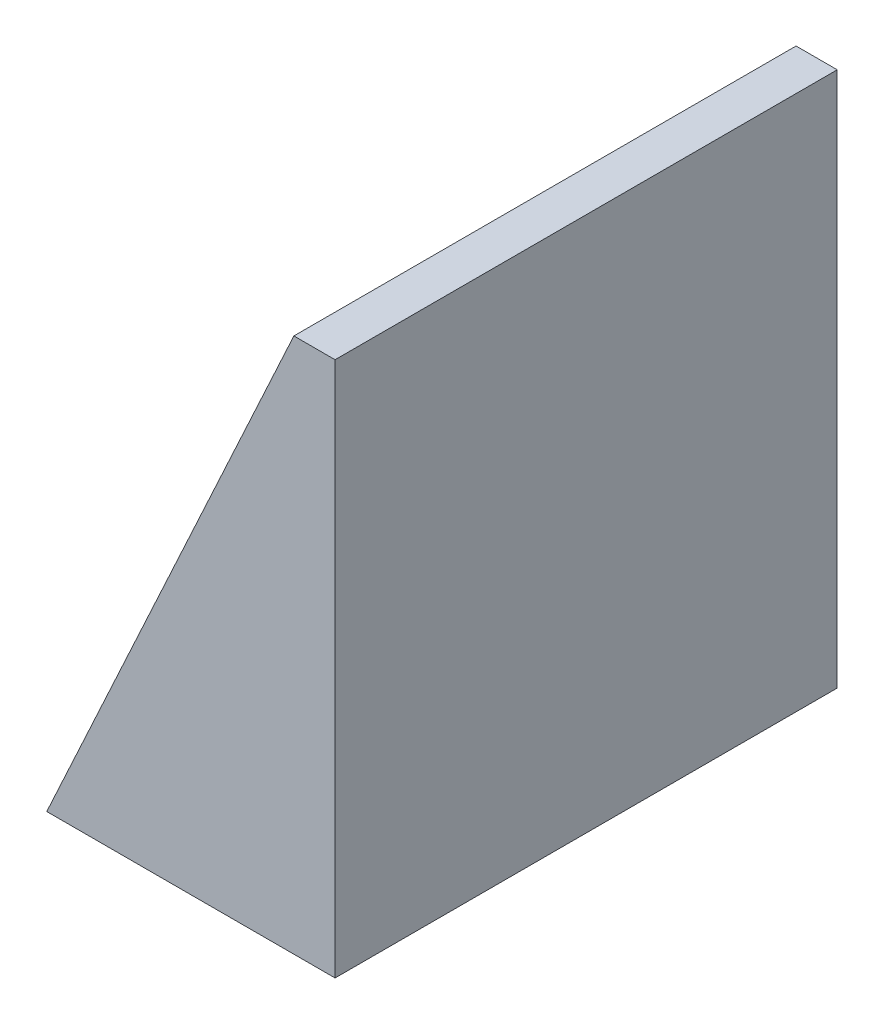
SolidWorks part; units mm, degrees
ref_plane "Front Plane" through (0, 0, 0) normal (0, 0, 1) x (1, 0, 0)
ref_plane "Top Plane" through (0, 0, 0) normal (0, 1, 0) x (1, 0, 0)
ref_plane "Right Plane" through (0, 0, 0) normal (1, 0, 0) x (0, 0, -1)
sketch "Sketch1" plane through (0, 0, 0) normal (0, 0, 1) x (1, 0, 0)
  line L0 (0, 0) -> (50, 0)
  line L1 (50, 0) -> (50, -650)
  line L2 (50, -650) -> (-300, -650)
  line L3 (-300, -650) -> (0, 0)
extrude "Boss-Extrude1" add sketch "Sketch1" along normal blind 609.6
